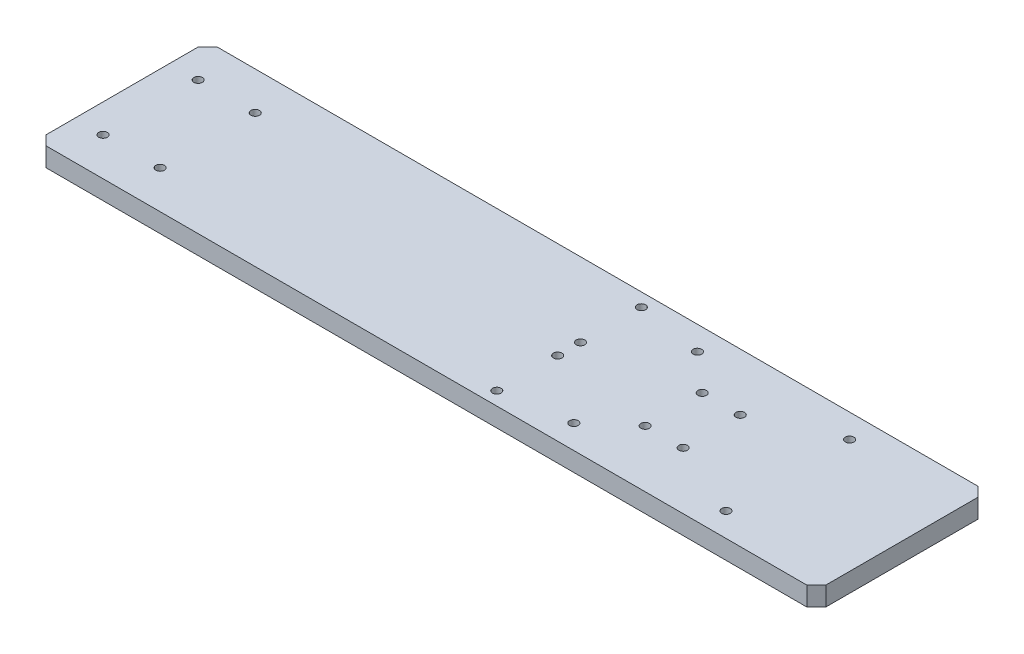
SolidWorks part; units mm, degrees
material "Acrílico (Impacto medio-alto)"
ref_plane "Front Plane" through (0, 0, 0) normal (0, 0, 1) x (1, 0, 0)
ref_plane "Top Plane" through (0, 0, 0) normal (0, 1, 0) x (1, 0, 0)
ref_plane "Right Plane" through (0, 0, 0) normal (1, 0, 0) x (0, 0, -1)
sketch "Croquis1" plane through (0, 0, 0) normal (0, 1, 0) x (1, 0, 0)
  line L1 (0, -45) -> (410, -45)
  line L2 (0, -45) -> (0, 45)
  line L3 (0, 45) -> (410, 45)
  line L4 (410, -45) -> (410, 45)
  line L5 (0, -45) -> (410, 45) construction
  line L6 (0, 45) -> (410, -45) construction
  dimension "D1" = 410
  dimension "D2" = 90
extrude "Saliente-Extruir1" add sketch "Croquis1" along normal blind 10
chamfer "Chaflán1" distance 5 angle 45 4 edges at (0, 5, -45) (0, 5, 45) (410, 5, 45) (410, 5, -45)
hole_wizard "Avellanado para tornillo con cabeza avellanada de clavija hexagonal de M41" positions "Croquis2" profile "Croquis3" countersink size "M4" standard "DIN" end condition through all
sketch "Croquis2" plane through (0, 0, 0) normal (0, -1, 0) x (-1, 0, 0)
  line L1 (-45, 25) -> (-15, 25) construction
  line L2 (-45, 25) -> (-45, -25) construction
  line L3 (-45, -25) -> (-15, -25) construction
  line L4 (-15, 25) -> (-15, -25) construction
  line L5 (-45, 25) -> (-15, -25) construction
  line L6 (-45, -25) -> (-15, 25) construction
  line L9 (-55, 35) -> (-5, 35) construction
  line L10 (-55, 35) -> (-55, -35) construction
  line L11 (-55, -35) -> (-5, -35) construction
  line L12 (-5, 35) -> (-5, -35) construction
  line L13 (-55, 35) -> (-5, -35) construction
  line L14 (-55, -35) -> (-5, 35) construction
  point P2 (-15, -25)
  point P5 (-45, 25)
  point P6 (-45, -25)
  point P7 (-15, 25)
  point P121 (-30, 0)
  point P203 (-30, 0)
  dimension "D1" = 30
  dimension "D2" = 50
  dimension "D3" = 50
  dimension "D4" = 70
  dimension "D5" = 5
sketch "Croquis3" plane through (15, 0, 25) normal (1, 0, 0) x (0, 0, -1)
  line L0 (0, 0) -> (0, 10)
  line L1 (0, 10) -> (2.25, 10)
  line L2 (2.25, 10) -> (2.25, 2.34)
  line L3 (2.25, 2.34) -> (4.59, 0)
  line L5 (4.59, 0) -> (0, 0)
  line L6 (-2.25, 2.34) -> (-4.59, 0) construction
  line L11 (0, -6.35) -> (0, 107.95) construction
  dimension "Diámetro de taladro hasta el siguiente" = 4.5
  dimension "Profundidad de taladro hasta el siguiente" = 10
  dimension "Diámetro de avellanado cercano" = 9.18
  dimension "Ángulo de avellanado cercano" = 90
hole_wizard "Avellanado para tornillo con cabeza avellanada de clavija hexagonal de M44" positions "Croquis4" profile "Croquis5" countersink size "M4" standard "DIN" end condition through all
sketch "Croquis4" plane through (0, 0, 0) normal (0, -1, 0) x (-1, 0, 0)
  line L0 (-235, 38) -> (-235, 6) construction
  line L2 (-235, -6) -> (-235, -38) construction
  line L4 (-235, 6) -> (-235, -6) construction
  line L5 (-55, 35) -> (-55, -35) construction
  point P1 (-235, 38)
  point P2 (-235, 6)
  point P5 (-235, -6)
  point P6 (-235, -38)
  point P16 (-235, 0)
  dimension "D1" = 32
  dimension "D2" = 12
  dimension "D3" = 180
sketch "Croquis5" plane through (235, 0, -38) normal (1, 0, 0) x (0, 0, -1)
  line L0 (0, 0) -> (0, 10)
  line L1 (0, 10) -> (2.25, 10)
  line L2 (2.25, 10) -> (2.25, 2.34)
  line L3 (2.25, 2.34) -> (4.59, 0)
  line L5 (4.59, 0) -> (0, 0)
  line L6 (-2.25, 2.34) -> (-4.59, 0) construction
  line L11 (0, -6.35) -> (0, 107.95) construction
  dimension "Diámetro de taladro hasta el siguiente" = 4.5
  dimension "Profundidad de taladro hasta el siguiente" = 10
  dimension "Diámetro de avellanado cercano" = 9.18
  dimension "Ángulo de avellanado cercano" = 90
hole_wizard "Avellanado para tornillo con cabeza avellanada de clavija hexagonal de M42" positions "Croquis6" profile "Croquis7" countersink size "M4" standard "DIN" end condition through all
sketch "Croquis6" plane through (0, 0, 0) normal (0, -1, 0) x (-1, 0, 0)
  line L1 (-310, -15) -> (-290, -15) construction
  line L2 (-310, -15) -> (-310, 15) construction
  line L3 (-310, 15) -> (-290, 15) construction
  line L4 (-290, -15) -> (-290, 15) construction
  line L5 (-310, -15) -> (-290, 15) construction
  line L6 (-310, 15) -> (-290, -15) construction
  line L7 (-55, 35) -> (-55, -35) construction
  point P2 (-290, 15)
  point P5 (-310, -15)
  point P6 (-310, 15)
  point P7 (-290, -15)
  point P41 (-300, 0)
  dimension "D1" = 235
  dimension "D2" = 20
  dimension "D3" = 30
sketch "Croquis7" plane through (290, 0, -15) normal (1, 0, 0) x (0, 0, -1)
  line L0 (0, 0) -> (0, 10)
  line L1 (0, 10) -> (2.25, 10)
  line L2 (2.25, 10) -> (2.25, 2.34)
  line L3 (2.25, 2.34) -> (4.59, 0)
  line L5 (4.59, 0) -> (0, 0)
  line L6 (-2.25, 2.34) -> (-4.59, 0) construction
  line L11 (0, -6.35) -> (0, 107.95) construction
  dimension "Diámetro de taladro hasta el siguiente" = 4.5
  dimension "Profundidad de taladro hasta el siguiente" = 10
  dimension "Diámetro de avellanado cercano" = 9.18
  dimension "Ángulo de avellanado cercano" = 90
hole_wizard "Avellanado para tornillo con cabeza avellanada de clavija hexagonal de M43" positions "Croquis8" profile "Croquis9" countersink size "M4" standard "DIN" end condition through all
sketch "Croquis8" plane through (0, 0, 0) normal (0, -1, 0) x (-1, 0, 0)
  line L1 (-350, -32.5) -> (-270, -32.5)
  line L2 (-350, -32.5) -> (-350, 32.5)
  line L3 (-350, 32.5) -> (-270, 32.5)
  line L4 (-270, -32.5) -> (-270, 32.5)
  line L5 (-350, -32.5) -> (-270, 32.5) construction
  line L6 (-350, 32.5) -> (-270, -32.5) construction
  point P2 (-270, 32.5)
  point P5 (-350, -32.5)
  point P6 (-350, 32.5)
  point P7 (-270, -32.5)
  point P23 (-310, 0)
  dimension "D1" = 80
  dimension "D2" = 65
  dimension "D3" = 270
sketch "Croquis9" plane through (270, 0, -32.5) normal (1, 0, 0) x (0, 0, -1)
  line L0 (0, 0) -> (0, 10)
  line L1 (0, 10) -> (2.25, 10)
  line L2 (2.25, 10) -> (2.25, 2.34)
  line L3 (2.25, 2.34) -> (4.59, 0)
  line L5 (4.59, 0) -> (0, 0)
  line L6 (-2.25, 2.34) -> (-4.59, 0) construction
  line L11 (0, -6.35) -> (0, 107.95) construction
  dimension "Diámetro de taladro hasta el siguiente" = 4.5
  dimension "Profundidad de taladro hasta el siguiente" = 10
  dimension "Diámetro de avellanado cercano" = 9.18
  dimension "Ángulo de avellanado cercano" = 90
